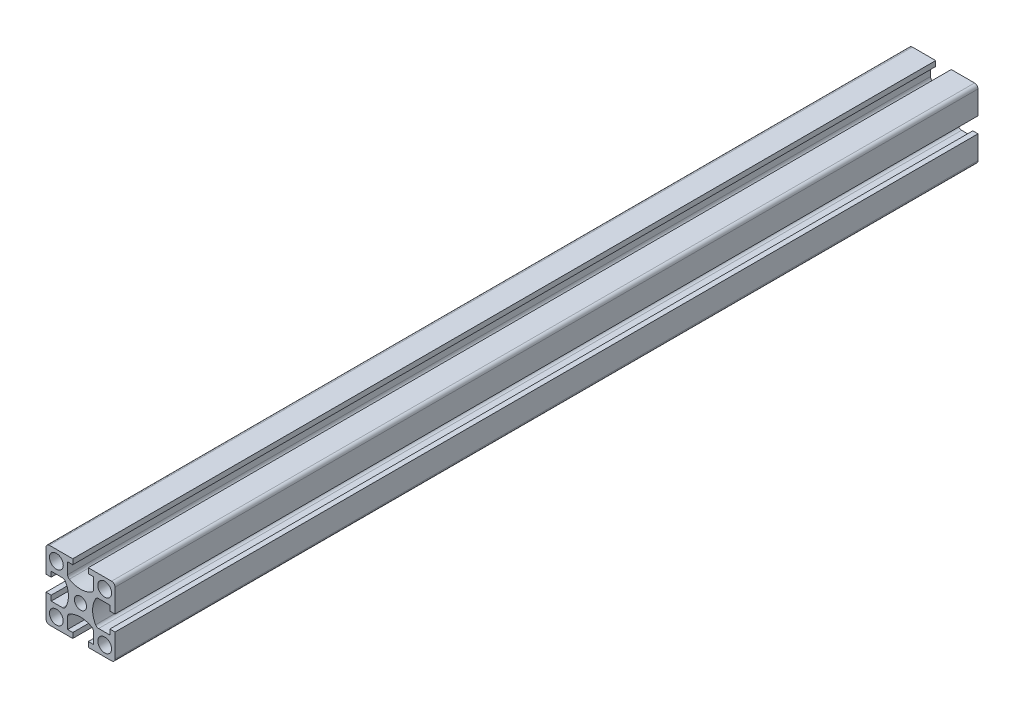
SolidWorks part; units mm, degrees
ref_plane "Front Plane" through (0, 0, 0) normal (0, 0, 1) x (1, 0, 0)
ref_plane "Top Plane" through (0, 0, 0) normal (0, 1, 0) x (1, 0, 0)
ref_plane "Right Plane" through (0, 0, 0) normal (1, 0, 0) x (0, 0, -1)
sketch "Sketch1" plane through (0, 0, 0) normal (0, 0, 1) x (1, 0, 0)
  line L64 (-10, 9) -> (-10, 2.25)
  line L65 (-10, 2.25) -> (-8.5, 2.25)
  line L66 (-8.5, 2.25) -> (-8.5, 3.75)
  line L67 (-8.5, 3.75) -> (-5.2369, 3.75)
  line L68 (-5.2369, -3.75) -> (-8.5, -3.75)
  line L69 (-8.5, -3.75) -> (-8.5, -2.25)
  line L70 (-8.5, -2.25) -> (-10, -2.25)
  line L71 (-10, -2.25) -> (-10, -9)
  line L72 (-9, -10) -> (-2.25, -10)
  line L73 (-2.25, -10) -> (-2.25, -8.5)
  line L74 (-2.25, -8.5) -> (-3.75, -8.5)
  line L75 (-3.75, -8.5) -> (-3.75, -5.2369)
  line L76 (3.75, -5.2369) -> (3.75, -8.5)
  line L77 (3.75, -8.5) -> (2.25, -8.5)
  line L78 (2.25, -8.5) -> (2.25, -10)
  line L79 (2.25, -10) -> (9, -10)
  line L80 (10, -9) -> (10, -2.25)
  line L81 (10, -2.25) -> (8.5, -2.25)
  line L82 (8.5, -2.25) -> (8.5, -3.75)
  line L83 (8.5, -3.75) -> (5.2369, -3.75)
  line L84 (5.2369, 3.75) -> (8.5, 3.75)
  line L85 (8.5, 3.75) -> (8.5, 2.25)
  line L86 (8.5, 2.25) -> (10, 2.25)
  line L87 (10, 2.25) -> (10, 9)
  line L88 (9, 10) -> (2.25, 10)
  line L89 (2.25, 10) -> (2.25, 8.5)
  line L90 (2.25, 8.5) -> (3.75, 8.5)
  line L91 (3.75, 8.5) -> (3.75, 5.2369)
  line L92 (-3.75, 5.2369) -> (-3.75, 8.5)
  line L93 (-3.75, 8.5) -> (-2.25, 8.5)
  line L94 (-2.25, 8.5) -> (-2.25, 10)
  line L95 (-2.25, 10) -> (-9, 10)
  circle A5 centre (-7, -7) radius 2
  circle A6 centre (7, -7) radius 2
  circle A7 centre (7, 7) radius 2
  circle A8 centre (0, 0) radius 1.75
  circle A9 centre (-7, 7) radius 2
  arc A32 (-9, 10) -> (-10, 9) centre (-9, 9) ccw
  arc A33 (-4.3708, 3.25) -> (-5.2369, 3.75) centre (-5.2369, 2.75) ccw
  arc A34 (-4.3708, -3.25) -> (-4.3708, 3.25) centre (-10, 0) ccw
  arc A35 (-5.2369, -3.75) -> (-4.3708, -3.25) centre (-5.2369, -2.75) ccw
  arc A36 (-10, -9) -> (-9, -10) centre (-9, -9) ccw
  arc A37 (-3.25, -4.3708) -> (-3.75, -5.2369) centre (-2.75, -5.2369) ccw
  arc A38 (3.25, -4.3708) -> (-3.25, -4.3708) centre (0, -10) ccw
  arc A39 (3.75, -5.2369) -> (3.25, -4.3708) centre (2.75, -5.2369) ccw
  arc A40 (9, -10) -> (10, -9) centre (9, -9) ccw
  arc A41 (4.3708, -3.25) -> (5.2369, -3.75) centre (5.2369, -2.75) ccw
  arc A42 (4.3708, 3.25) -> (4.3708, -3.25) centre (10, 0) ccw
  arc A43 (5.2369, 3.75) -> (4.3708, 3.25) centre (5.2369, 2.75) ccw
  arc A44 (10, 9) -> (9, 10) centre (9, 9) ccw
  arc A45 (3.25, 4.3708) -> (3.75, 5.2369) centre (2.75, 5.2369) ccw
  arc A46 (-3.25, 4.3708) -> (3.25, 4.3708) centre (0, 10) ccw
  arc A47 (-3.75, 5.2369) -> (-3.25, 4.3708) centre (-2.75, 5.2369) ccw
extrude "Boss-Extrude1" add sketch "Sketch1" along normal blind 250
